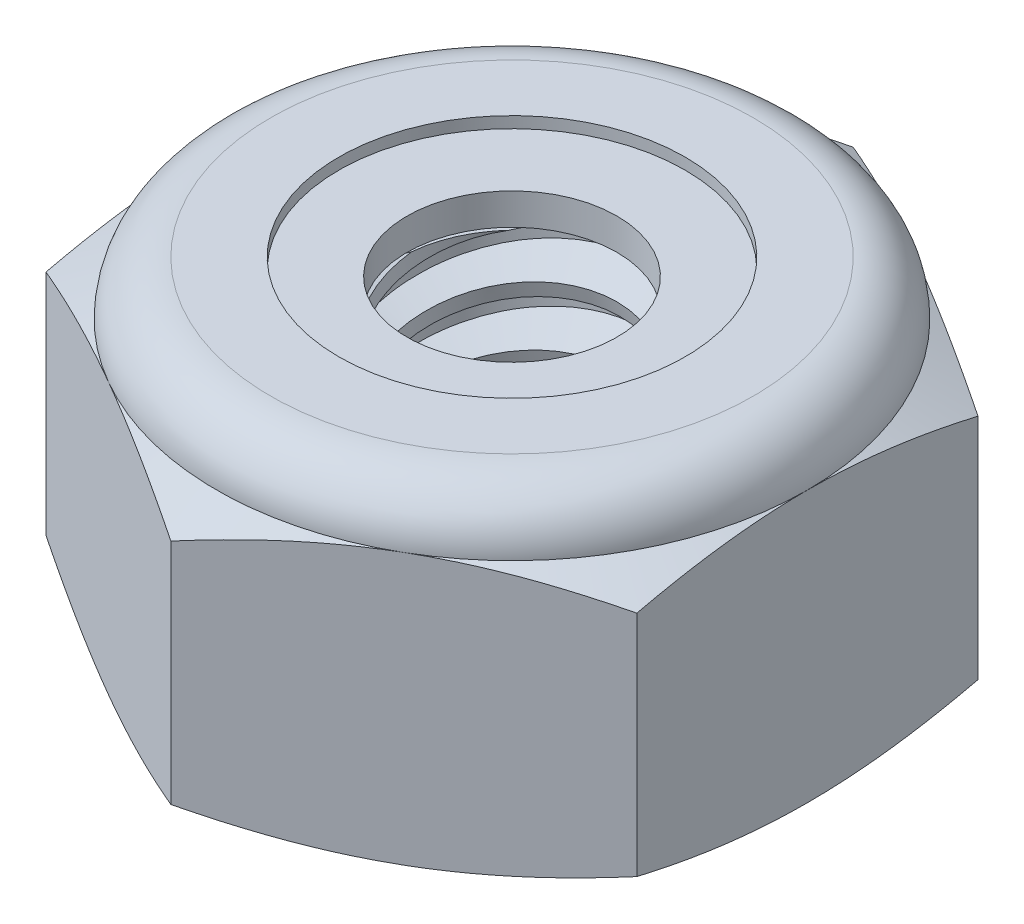
SolidWorks part; units mm, degrees
ref_plane "Front" through (0, 0, 0) normal (0, 0, 1) x (1, 0, 0)
ref_plane "Top" through (0, 0, 0) normal (0, 1, 0) x (1, 0, 0)
ref_plane "Right" through (0, 0, 0) normal (1, 0, 0) x (0, 0, -1)
sketch "Sketch1" plane through (0, 0, 0) normal (0, 1, 0) x (1, 0, 0)
  line L1 (0, 4.5827) -> (-3.9688, 2.2914)
  line L2 (-3.9688, 2.2914) -> (-3.9688, -2.2914)
  line L3 (-3.9688, -2.2914) -> (0, -4.5827)
  line L4 (0, -4.5827) -> (3.9687, -2.2914)
  line L5 (3.9687, -2.2914) -> (3.9687, 2.2914)
  line L6 (3.9687, 2.2914) -> (0, 4.5827)
  circle A0 centre (0, 0) radius 3.9688 construction
  dimension "Hex Flats" = 7.9375
extrude "Extrude1" add sketch "Sketch1" along normal blind 4.3656
sketch "Sketch2" plane through (0, 0, 0) normal (1, 0, 0) x (0, 0, -1)
  line L0 (-1.7526, 0) -> (-1.7526, 4.3656) construction
  line L1 (0, 0) -> (1.7526, 0)
  line L2 (0, 0) -> (0, 4.3656)
  line L3 (0, 4.3656) -> (1.7526, 4.3656)
  line L4 (1.7526, 0) -> (1.7526, 4.3656)
  line L5 (-2.2914, 4.3656) -> (2.2914, 4.3656) construction
  line L7 (0, -1.7526) -> (0, 0) construction
  dimension "Thread Dia" = 3.5052
revolve "Revolve1" add sketch "Sketch2" angle 360 about L7
sketch "Sketch3" plane through (0, 0, 0) normal (1, 0, 0) x (0, 0, -1)
  line L0 (1.7526, 4.3656) -> (-1.7526, 4.3656) construction
  line L1 (-1.7526, 4.3656) -> (-1.7526, 3.5719) construction
  line L2 (-1.7526, 3.5719) -> (1.7526, 4.3656) construction
  line L3 (1.7526, 4.3656) -> (1.7745, 4.2689) construction
  line L4 (1.7745, 4.2689) -> (1.9279, 3.5915)
  line L5 (1.9279, 3.5915) -> (1.4541, 3.7385)
  line L6 (1.4541, 3.7385) -> (1.4103, 3.932)
  line L7 (1.4103, 3.932) -> (1.7745, 4.2689)
  line L8 (1.4322, 3.8353) -> (1.8512, 3.9302) construction
  line L9 (1.7526, 4.3656) -> (1.7526, 3.9078) construction
  line L10 (1.7526, 3.9078) -> (-1.7526, 3.1141) construction
  line L11 (-1.7526, 3.1141) -> (-1.7526, 3.5719) construction
  line L12 (-0.1935, 4.3656) -> (0.1935, 2.6563) construction
  line L13 (-1.7526, 0) -> (-1.7526, 4.3656) construction
  line L14 (0, 4.3656) -> (1.7526, 4.3656) construction
  line L15 (1.7526, 0) -> (1.7526, 4.3656) construction
  point P13 (0, 3.511)
  dimension "D1" = 0.0992
  dimension "D2" = 0.1984
  dimension "Thread Pitch" = 0.7937
  dimension "D4" = 60
  dimension "D5" = 0.7937
revolve "Cut-Revolve1" cut sketch "Sketch3" angle 360 about L12
pattern_linear "LPattern1" count 6 spacing 0.7937 along (0, -1, 0) count 2 spacing 0.7937 along (0, 1, 0) of "Cut-Revolve1"
sketch "Sketch4" plane through (0, 0, 0) normal (1, 0, 0) x (0, 0, -1)
  line L0 (0, 4.3656) -> (1.7526, 4.3656)
  line L1 (1.7526, 4.3656) -> (1.4103, 4.206)
  line L2 (1.4103, 4.206) -> (1.4103, 0.1596)
  line L3 (1.4103, 0.1596) -> (1.7526, 0)
  line L4 (1.7526, 0) -> (0, 0)
  line L5 (0, 0) -> (0, 4.3656)
  line L6 (1.7526, 0) -> (1.7526, 4.3656) construction
  line L7 (0, 4.3656) -> (1.7526, 4.3656) construction
  line L8 (0, 0) -> (1.7526, 0) construction
  line L9 (0, 0) -> (0, 4.3656) construction
  line L10 (0, 4.3656) -> (0, 4.7433) construction
  dimension "D1" = 25
revolve "Cut-Revolve2" cut sketch "Sketch4" angle 360 about L10
combine bodies "Combine1" operation type subtract main body 112 bodies to subtract 111
sketch "Sketch5" plane through (0, 0, 0) normal (1, 0, 0) x (0, 0, -1)
  line L0 (0, 0) -> (3.9688, 0)
  line L1 (3.9688, 0) -> (4.5827, 0.2863)
  line L2 (4.5827, 0.2863) -> (4.5827, 3.3517)
  line L3 (4.5827, 3.3517) -> (3.9688, 3.638)
  line L4 (3.2411, 4.3656) -> (3.2411, 5.6356)
  line L5 (3.2411, 5.6356) -> (5.8527, 5.6356)
  line L6 (5.8527, 5.6356) -> (5.8527, -1.27)
  line L7 (5.8527, -1.27) -> (0, -1.27)
  line L8 (0, -1.27) -> (0, 0)
  line L9 (3.9688, 3.638) -> (3.9688, 0) construction
  line L10 (0, 0) -> (1.7526, 0) construction
  line L13 (4.5827, 1.819) -> (5.8527, 1.819) construction
  line L14 (4.5827, 4.3656) -> (4.5827, 0) construction
  line L15 (0, 0) -> (0, 5.6356) construction
  line L20 (0, 5.6356) -> (3.2411, 5.6356) construction
  line L22 (0, 4.3656) -> (1.7526, 4.3656) construction
  arc A0 (3.9688, 3.638) -> (3.2411, 4.3656) centre (3.2411, 3.638) ccw
  dimension "D1" = 25
  dimension "D2" = 1.27
  dimension "D3" = 4.3656
  dimension "D4" = 0.7276
revolve "Cut-Revolve3" cut sketch "Sketch5" angle 360 about L15
sketch "Sketch6" plane through (0, 0, 0) normal (1, 0, 0) x (0, 0, -1)
  line L0 (0, 3.638) -> (3.8163, 3.638)
  line L1 (3.2411, 4.2132) -> (2.3257, 4.2132)
  line L2 (0, 5.6356) -> (0, 3.638)
  line L3 (2.3257, 5.6356) -> (0, 5.6356)
  line L4 (0, 5.6356) -> (3.2411, 5.6356) construction
  line L5 (0, 0) -> (0, 5.6356) construction
  line L6 (0, 5.6356) -> (0, 44.323) construction
  line L7 (2.3257, 4.2132) -> (2.3257, 5.6356)
  line L8 (3.2411, 4.3656) -> (3.2411, 4.2132) construction
  line L9 (2.3257, 4.2132) -> (1.4103, 4.2132) construction
  line L10 (1.4103, 4.2132) -> (1.4103, 4.206) construction
  arc A0 (3.8163, 3.638) -> (3.2411, 4.2132) centre (3.2411, 3.638) ccw
  arc A1 (3.9688, 3.638) -> (3.2411, 4.3656) centre (3.2411, 3.638) ccw construction
  dimension "D1" = 0.1524
revolve "Cut-Revolve4" cut sketch "Sketch6" angle 360 about L6
sketch "Sketch7" plane through (0, 0, 0) normal (1, 0, 0) x (0, 0, -1)
  line L0 (1.4103, 3.7142) -> (3.7343, 3.7142)
  line L1 (3.2411, 4.137) -> (1.4103, 4.137)
  line L2 (1.4103, 4.137) -> (1.4103, 3.7142)
  line L3 (1.4103, 3.7142) -> (0, 3.7142) construction
  line L4 (0, 3.7142) -> (0, 4.137) construction
  line L5 (0, 4.137) -> (1.4103, 4.137) construction
  line L6 (1.4103, 3.7142) -> (1.4103, 3.638) construction
  line L7 (0, 3.638) -> (3.8163, 3.638) construction
  line L8 (3.2411, 4.137) -> (3.2411, 4.2132) construction
  arc A0 (3.7343, 3.7142) -> (3.2411, 4.137) centre (3.2411, 3.638) ccw
  arc A2 (3.8163, 3.638) -> (3.2411, 4.2132) centre (3.2411, 3.638) ccw construction
  dimension "D1" = 0.0762
revolve "Revolve2" add sketch "Sketch7" angle 360 about L4
equation "\"D1@Sketch3\"=\"Thread Pitch@Sketch3\"/8"
equation "\"D2@Sketch3\"=\"Thread Pitch@Sketch3\"/4"
equation "\"D5@Sketch3\"=\"Thread Pitch@Sketch3\""
equation "\"D4@LPattern1\"=\"Thread Pitch@Sketch3\""
equation "\"D3@LPattern1\"=\"Thread Pitch@Sketch3\""
equation "\"D1@LPattern1\"=\"Height@Extrude1\"/\"Thread Pitch@Sketch3\""
equation "\"D4@Sketch5\"=\"Height@Extrude1\"/6"
